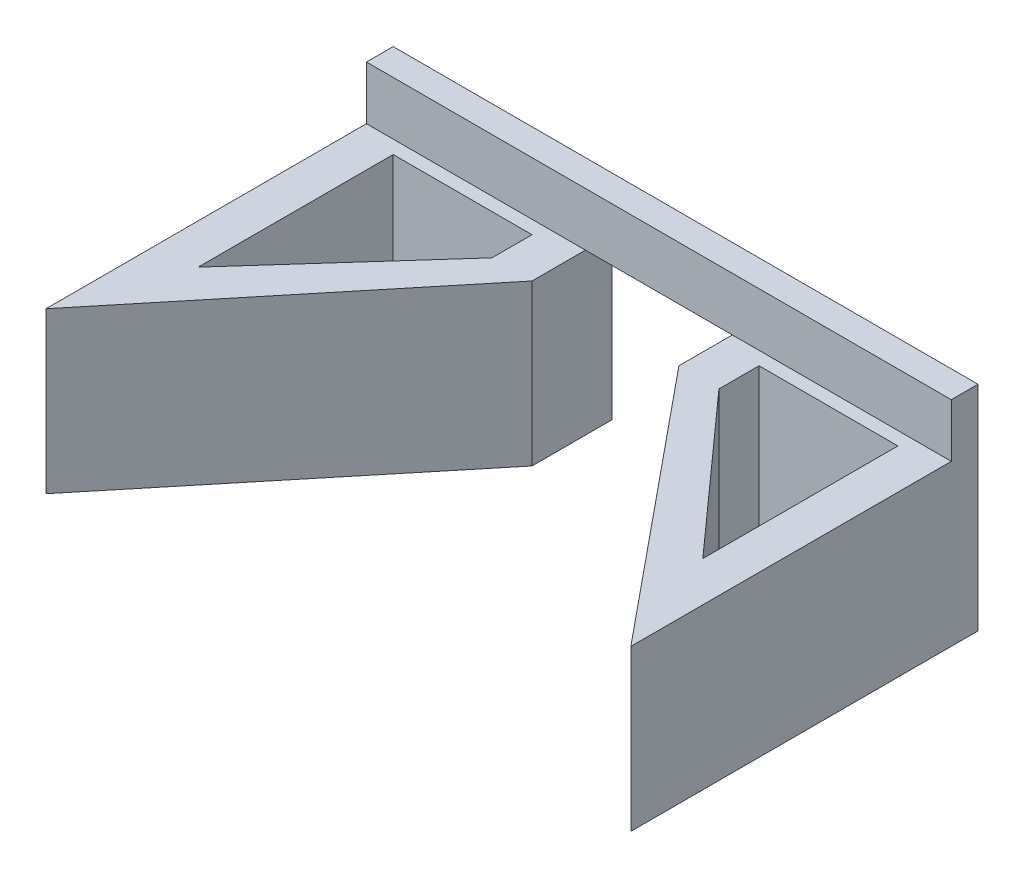
SolidWorks part; units mm, degrees
ref_plane "Front Plane" through (0, 0, 0) normal (0, 0, 1) x (1, 0, 0)
ref_plane "Top Plane" through (0, 0, 0) normal (0, 1, 0) x (1, 0, 0)
ref_plane "Right Plane" through (0, 0, 0) normal (1, 0, 0) x (0, 0, -1)
sketch "Sketch1" plane through (0, 0, 0) normal (0, 1, 0) x (1, 0, 0)
  line L0 (0, 30.1707) -> (0, -30.4719) construction
  line L1 (0, -30.4719) -> (0, 0) construction
  line L2 (0, 0) -> (-49.1968, 0) construction
  line L3 (-49.1968, 0) -> (52.6104, 0) construction
  line L4 (-109.5, 12.7008) -> (-109.5, -87.2992)
  line L5 (-109.5, -87.2992) -> (-27.5, 12.7008)
  line L13 (-109.5, 42.7008) -> (-27.5, 42.7008)
  line L14 (-27.5, 12.7008) -> (-27.5, 42.7008)
  line L20 (-109.5, 42.7008) -> (-109.5, 12.7008)
  line L26 (-94.5, 27.7008) -> (-94.5, -45.3502)
  line L27 (-94.5, -45.3502) -> (-42.5, 12.7008)
  line L28 (-42.5, 12.7008) -> (-42.5, 27.7008)
  line L29 (-42.5, 27.7008) -> (-94.5, 27.7008)
  line L30 (42.5, 12.7008) -> (42.5, 27.7008)
  line L31 (94.5, -45.3502) -> (42.5, 12.7008)
  line L32 (94.5, 27.7008) -> (94.5, -45.3502)
  line L33 (42.5, 27.7008) -> (94.5, 27.7008)
  line L34 (109.5, 42.7008) -> (27.5, 42.7008)
  line L35 (27.5, 12.7008) -> (27.5, 42.7008)
  line L36 (109.5, -87.2992) -> (27.5, 12.7008)
  line L37 (109.5, 12.7008) -> (109.5, -87.2992)
  line L38 (109.5, 42.7008) -> (109.5, 12.7008)
  dimension "D1" = 27.5
  dimension "D2" = 82
  dimension "D3" = 100
  dimension "D4" = 30
  dimension "D5" = 15
  dimension "D6" = 15
  dimension "D7" = 15
  dimension "D8" = 15
extrude "Boss-Extrude1" add sketch "Sketch1" along normal blind 60
sketch "Sketch3" plane through (0, 60, 0) normal (0, 1, 0) x (1, 0, 0)
  line L0 (109.5, -87.2992) -> (109.5, 42.7008) construction
  line L1 (-109.5, 42.7008) -> (109.5, 42.7008)
  line L2 (-109.5, 42.7008) -> (-109.5, 32.7008)
  line L3 (-109.5, 32.7008) -> (109.5, 32.7008)
  line L4 (109.5, 42.7008) -> (109.5, 32.7008)
  dimension "D1" = 10
extrude "Boss-Extrude3" add sketch "Sketch3" along normal blind 20
